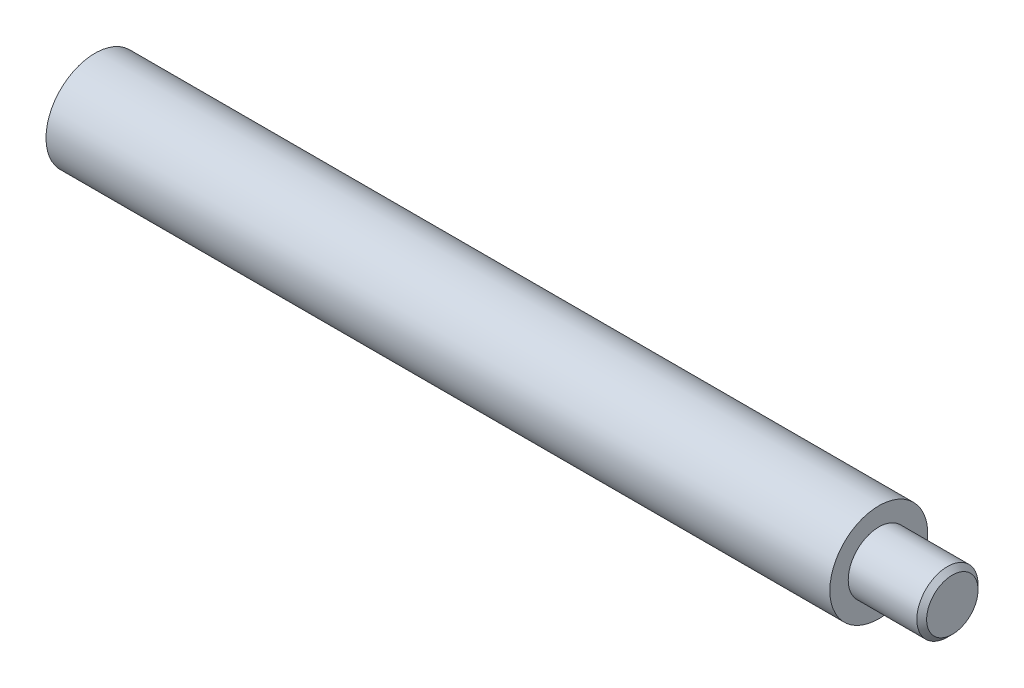
SolidWorks part; units mm, degrees
material "1.4305 (X8CrNiS18-9)"
ref_plane "Vorne" through (0, 0, 0) normal (0, 0, 1) x (1, 0, 0)
ref_plane "Oben" through (0, 0, 0) normal (0, 1, 0) x (1, 0, 0)
ref_plane "Rechts" through (0, 0, 0) normal (1, 0, 0) x (0, 0, -1)
sketch "Skizze1" plane through (0, 0, 0) normal (0, 0, 1) x (1, 0, 0)
  line L0 (2.2, 0) -> (-2.2, 0) construction
  line L1 (19, 0) -> (-16, 0)
  line L2 (16, 1.25) -> (16, 2)
  line L3 (16, 2) -> (-16, 2)
  line L4 (-16, 0) -> (-16, 2)
  line L5 (0, 0) -> (19.6031, 0) construction
  line L6 (0, -2.2) -> (0, 2.2) construction
  line L10 (16, 1.25) -> (19, 1.25)
  line L11 (19, 0) -> (19, 1.25)
  point P9 (0, 2)
  dimension "D1" = 4
  dimension "D2" = 32
  dimension "D3" = 2.5
  dimension "D4" = 3
revolve "Rotation1" add sketch "Skizze1" angle 360 about L5
hole_wizard "M3 Gewindebohrung1" positions "Skizze2" profile "Skizze3" tap size "M3" standard "DIN"
sketch "Skizze2" plane through (-16, 0, 0) normal (-1, 0, 0) x (0, 0, 1)
  point P0 (0, 0)
sketch "Skizze3" plane through (-16, 0, 0) normal (0, 1, 0) x (0, 0, 1)
  line L0 (0, 0) -> (0, 7.2511)
  line L1 (0, 7.2511) -> (1.25, 6.5)
  line L2 (1.25, 6.5) -> (1.25, 0)
  line L5 (1.25, 0) -> (0, 0)
  line L10 (0, 7.2511) -> (-1.25, 6.5) construction
  line L11 (0, -6.35) -> (0, 107.95) construction
  dimension "Bohrerdurchmesser" = 2.5
  dimension "Bohrungstiefe" = 6.5
  dimension "Spitzenwinkel" = 118
cosmetic thread "Bohrungsgewinde1" parameters "D1"=4, "D2"=3
chamfer "Fase1" distance 0.2 angle 45 1 edges at (19, 0, 1.25)
